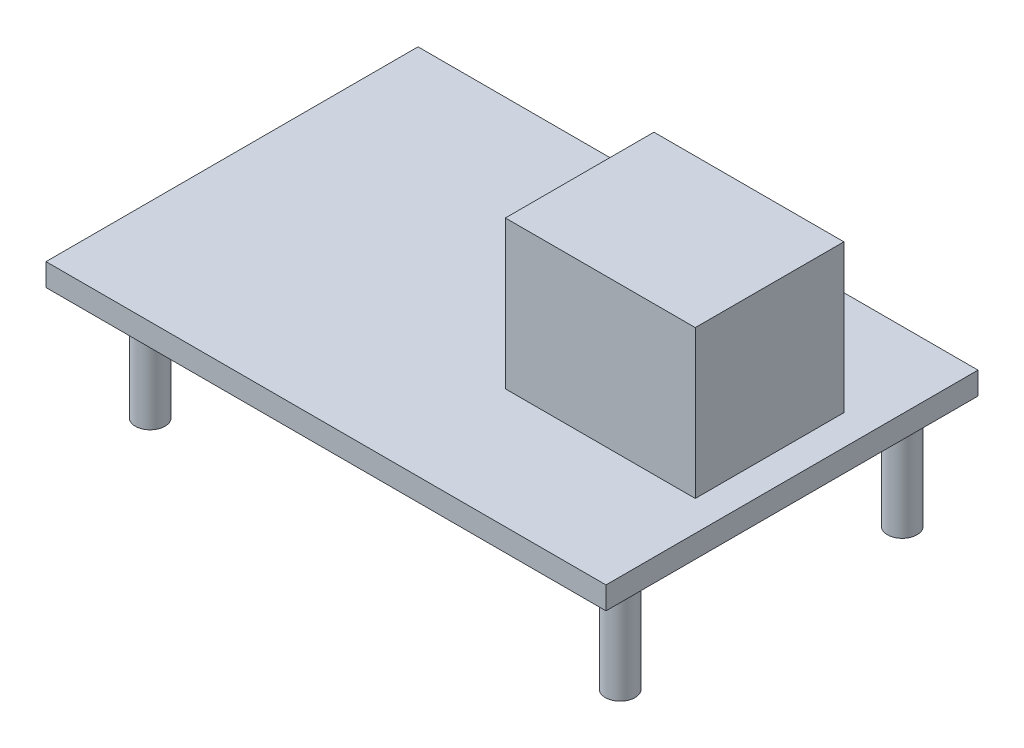
SolidWorks part; units mm, degrees
ref_plane "Front Plane" through (0, 0, 0) normal (0, 0, 1) x (1, 0, 0)
ref_plane "Top Plane" through (0, 0, 0) normal (0, 1, 0) x (1, 0, 0)
ref_plane "Right Plane" through (0, 0, 0) normal (1, 0, 0) x (0, 0, -1)
sketch "Sketch1" plane through (0, 0, 0) normal (0, 1, 0) x (1, 0, 0)
  line L1 (0, 0) -> (18.92, 0)
  line L2 (0, 0) -> (0, -12.57)
  line L3 (0, -12.57) -> (18.92, -12.57)
  line L4 (18.92, 0) -> (18.92, -12.57)
  dimension "D1" = 18.92
  dimension "D2" = 12.57
extrude "Boss-Extrude1" add sketch "Sketch1" along normal blind 0.76
sketch "Sketch2" plane through (0, 0, 0) normal (0, -1, 0) x (-1, 0, 0)
  line L0 (-9.46, -12.57) -> (-9.46, 0) construction
  line L1 (0, -12.57) -> (-18.92, -12.57) construction
  line L2 (-18.92, 0) -> (0, 0) construction
  line L3 (-2.02, -12.57) -> (-2.02, 0) construction
  line L4 (0, 0) -> (0, -12.57) construction
  line L5 (-18.92, -11.07) -> (0, -11.07) construction
  line L6 (-18.92, -12.57) -> (-18.92, 0) construction
  line L7 (-17.9, -12.57) -> (-17.9, 0) construction
  circle A0 centre (-2.02, -11.07) radius 0.5
  circle A1 centre (-17.9, -11.07) radius 0.5
  circle A2 centre (-2.02, -7.89) radius 0.5
  circle A3 centre (-2.02, -1.54) radius 0.5
  circle A4 centre (-17.9, -1.54) radius 0.5
  point P24 (-17.9, -11.07)
  dimension "D4" = 1
  dimension "D5" = 1
  dimension "D6" = 3.18
  dimension "D7" = 1
  dimension "D9" = 1
  dimension "D1" = 2.02
  dimension "D2" = 1.5
  dimension "D3" = 15.88
  dimension "D8" = 6.35
extrude "Boss-Extrude2" add sketch "Sketch2" along normal blind 3.55
sketch "Sketch3" plane through (0, 0.76, 0) normal (0, 1, 0) x (1, 0, 0)
  line L0 (17.9, -1.54) -> (17.9, -11.07) construction
  line L2 (17.9, -3.5122) -> (11.4837, -3.5122)
  line L3 (17.9, -3.5122) -> (17.9, -8.5325)
  line L4 (17.9, -8.5325) -> (11.4837, -8.5325)
  line L5 (11.4837, -3.5122) -> (11.4837, -8.5325)
extrude "Boss-Extrude3" add sketch "Sketch3" along normal blind 5
